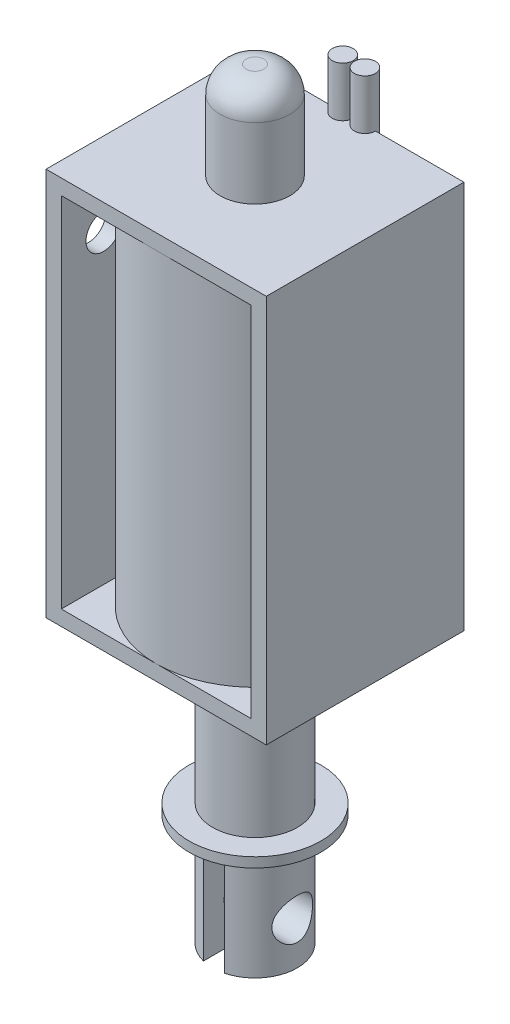
SolidWorks part; units mm, degrees
ref_plane "Front Plane" through (0, 0, 0) normal (0, 0, 1) x (1, 0, 0)
ref_plane "Top Plane" through (0, 0, 0) normal (0, 1, 0) x (1, 0, 0)
ref_plane "Right Plane" through (0, 0, 0) normal (1, 0, 0) x (0, 0, -1)
sketch "Sketch1" plane through (0, 0, 0) normal (0, 1, 0) x (1, 0, 0)
  line L1 (-8.445, 7.58) -> (8.445, 7.58)
  line L2 (-8.445, 7.58) -> (-8.445, -7.58)
  line L3 (-8.445, -7.58) -> (8.445, -7.58)
  line L4 (8.445, 7.58) -> (8.445, -7.58)
  line L5 (-8.445, 7.58) -> (8.445, -7.58) construction
  line L6 (-8.445, -7.58) -> (8.445, 7.58) construction
  point P1 (0, 0)
  dimension "D1" = 15.16
  dimension "D2" = 16.89
extrude "Boss-Extrude1" add sketch "Sketch1" along normal blind 29.8
sketch "Sketch2" plane through (0, 0, -7.58) normal (0, 0, -1) x (-1, 0, 0)
  line L0 (7.275, 28.63) -> (-7.275, 28.63)
  line L1 (-7.275, 28.63) -> (-7.275, 1.17)
  line L2 (-7.275, 1.17) -> (7.275, 1.17)
  line L3 (7.275, 1.17) -> (7.275, 28.63)
  line L4 (-8.445, 0) -> (8.445, 0)
  line L5 (8.445, 0) -> (8.445, 29.8)
  line L6 (8.445, 29.8) -> (-8.445, 29.8)
  line L7 (-8.445, 29.8) -> (-8.445, 0)
  line L8 (-8.445, 0) -> (8.445, 0)
  line L9 (8.445, 0) -> (8.445, 29.8)
  line L10 (8.445, 29.8) -> (-8.445, 29.8)
  line L11 (-8.445, 29.8) -> (-8.445, 0)
  dimension "D1" = 0
  dimension "D2" = 1.17
extrude "Cut-Extrude1" cut sketch "Sketch2" against normal through all both and the other way through all contours L2 L3 L0 L1
sketch "Sketch3" plane through (0, 0, 0) normal (0, -1, 0) x (1, 0, 0)
  circle A0 centre (0, 0) radius 3.25
  dimension "D1" = 6.5
extrude "Boss-Extrude2" add sketch "Sketch3" along normal blind 21.2
sketch "Sketch4" plane through (0, -21.2, 0) normal (0, -1, 0) x (1, 0, 0)
  line L0 (0, 3.25) -> (0, -3.25) construction
  line L1 (-0.81, 3.1474) -> (-0.81, -3.1474)
  line L2 (0.81, 3.1474) -> (0.81, -3.1474)
  line L3 (0, 0) -> (0.81, 0.0047) construction
  line L4 (0, 0) -> (-0.81, 0) construction
  circle A0 centre (0, 0) radius 3.25 construction
  circle A1 centre (0, 0) radius 3.25 construction
  arc A2 (-0.81, -3.1474) -> (0.81, -3.1474) centre (0, 0) ccw
  arc A3 (0.81, 3.1474) -> (-0.81, 3.1474) centre (0, 0) ccw
  dimension "D1" = 1.62
extrude "Cut-Extrude2" cut sketch "Sketch4" against normal blind 7.51 and the other way through all
sketch "Sketch5" plane through (0, 0, 0) normal (1, 0, 0) x (0, 0, -1)
  line L1 (-3.1474, -21.2) -> (3.1474, -21.2) construction
  circle A0 centre (0, -17.94) radius 1.56
  dimension "D1" = 3.12
  dimension "D2" = 3.26
extrude "Cut-Extrude3" cut sketch "Sketch5" against normal through all both and the other way through all
sketch "Sketch6" plane through (0, 29.8, 0) normal (0, 1, 0) x (1, 0, 0)
  circle A0 centre (0, 0) radius 2.675
  dimension "D1" = 5.35
extrude "Boss-Extrude3" add sketch "Sketch6" along normal blind 7.41
fillet "Fillet1" radius 2 1 edges at (0, 37.21, 2.675)
sketch "Sketch7" plane through (0, 1.17, 0) normal (0, 1, 0) x (1, 0, 0)
  circle A0 centre (0, 0) radius 7.58
extrude "Boss-Extrude4" add sketch "Sketch7" along normal up to surface (27.46 mm away) up to face at (0, 28.63, 0)
sketch "Sketch8" plane through (0, 28.63, 0) normal (0, -1, 0) x (1, 0, 0)
  line L0 (-8.445, -7.58) -> (8.445, -7.58) construction
  line L1 (0, 0) -> (0, -10.2813) construction
  circle A0 centre (-0.85, -7.58) radius 0.805
  circle A1 centre (0.85, -7.58) radius 0.805
  point P10 (0, 0)
  dimension "D1" = 1.61
  dimension "D2" = 1.61
  dimension "D3" = 0.85
  dimension "D4" = 0.85
extrude "Boss-Extrude7" add sketch "Sketch8" against normal blind 5
fillet "Fillet2" radius 0.5 2 edges
sketch "Sketch9" plane through (-8.445, 0, 0) normal (-1, 0, 0) x (0, 0, 1)
  line L0 (7.58, 29.8) -> (7.58, 0) construction
  line L1 (-7.58, 29.8) -> (7.58, 29.8) construction
  line L2 (-7.58, 29.8) -> (-7.58, 0) construction
  line L3 (-7.58, 0) -> (7.58, 0) construction
  circle A0 centre (4.34, 24.65) radius 1.35
  circle A1 centre (-4.34, 5.02) radius 1.35
  point P10 (0, 0)
  dimension "D2" = 2.7
  dimension "D1" = 3.24
  dimension "D3" = 5.15
  dimension "D4" = 3.24
  dimension "D5" = 5.02
extrude "Cut-Extrude4" cut sketch "Sketch9" against normal up to surface (1.17 mm away) and the other way through all up to face at (-7.275, 14.9, -4.8543)
sketch "Sketch10" plane through (0, -21.2, 0) normal (0, -1, 0) x (1, 0, 0)
  circle A0 centre (0, 0) radius 5.055
  dimension "D1" = 10.11
extrude "Boss-Extrude8" add sketch "Sketch10" against normal blind 0.75 from offset 8.58
